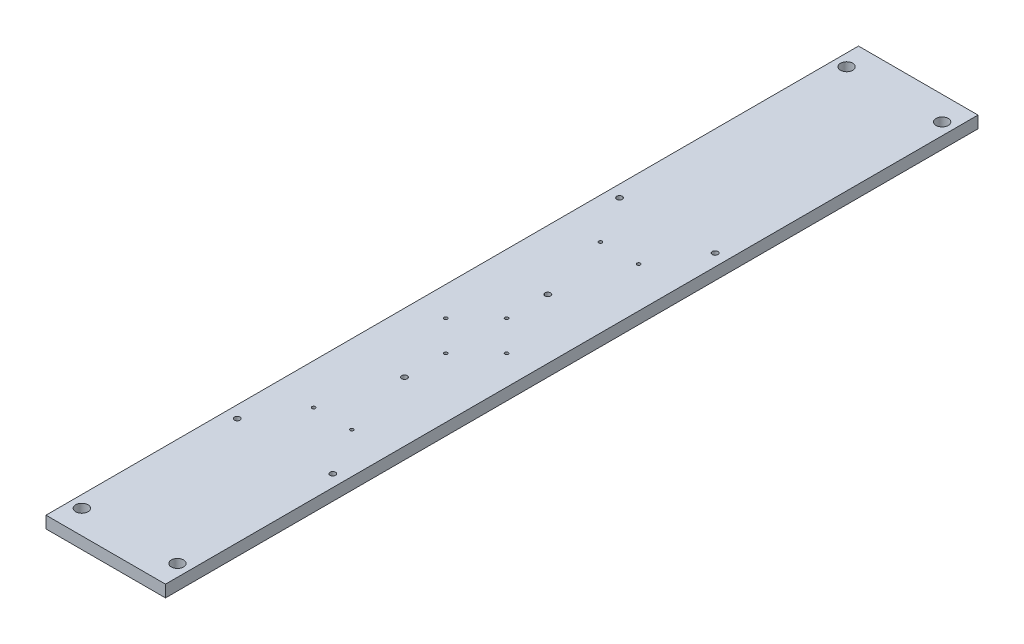
SolidWorks part; units mm, degrees
ref_plane "Front" through (0, 0, 0) normal (0, 0, 1) x (1, 0, 0)
ref_plane "Top" through (0, 0, 0) normal (0, 1, 0) x (1, 0, 0)
ref_plane "Right" through (0, 0, 0) normal (1, 0, 0) x (0, 0, -1)
sketch "Sketch1" plane through (0, 0, 0) normal (0, 1, 0) x (1, 0, 0)
  line L1 (0, 0) -> (63.5, 0)
  line L2 (0, 0) -> (0, 431.8)
  line L3 (0, 431.8) -> (63.5, 431.8)
  line L4 (63.5, 0) -> (63.5, 431.8)
  dimension "D1" = 431.8
  dimension "D2" = 63.5
extrude "Boss-Extrude1" add sketch "Sketch1" along normal blind 6.35
sketch "Sketch3" plane through (0, 6.35, 0) normal (0, 1, 0) x (1, 0, 0)
  line L0 (0, 0) -> (63.5, 0) construction
  line L1 (0, 431.8) -> (0, 0) construction
  line L2 (31.75, 431.8) -> (31.75, 0) construction
  line L3 (63.5, 431.8) -> (0, 431.8) construction
  line L6 (0, 165.1) -> (0, 228.6)
  line L9 (0, 196.85) -> (139.7, 196.85) construction
  circle A0 centre (3.175, 3.175) radius 1.1303
  circle A1 centre (3.175, 161.925) radius 1.1303
  circle A2 centre (3.175, 390.525) radius 1.1303
  circle A3 centre (3.175, 231.775) radius 1.1303
  circle A4 centre (60.325, 3.175) radius 1.1303
  circle A5 centre (60.325, 161.925) radius 1.1303
  circle A6 centre (60.325, 231.775) radius 1.1303
  circle A7 centre (60.325, 390.525) radius 1.1303
  dimension "D1" = 2.2606
  dimension "D2" = 3.175
  dimension "D3" = 3.175
  dimension "D5" = 63.5
  dimension "D4" = 2
sketch "Sketch6" plane through (0, 6.35, 0) normal (0, 1, 0) x (1, 0, 0)
  line L0 (63.5, 431.8) -> (0, 431.8) construction
  line L1 (0, 431.8) -> (0, 0) construction
  line L2 (31.75, 431.8) -> (31.75, 0) construction
  line L3 (0, 0) -> (63.5, 0) construction
  line L4 (31.75, 215.9) -> (94.2364, 215.9) construction
  circle A0 centre (6.35, 419.1) radius 3.2639
  circle A1 centre (57.15, 419.1) radius 3.2639
  circle A4 centre (57.15, 12.7) radius 3.2639
  circle A5 centre (6.35, 12.7) radius 3.2639
  point P13 (31.75, 215.9)
  dimension "D1" = 6.5278
  dimension "D2" = 12.7
  dimension "D3" = 6.35
extrude "Cut-Extrude9" cut sketch "Sketch6" against normal through all
sketch "Sketch7" plane through (0, 6.35, 0) normal (0, 1, 0) x (1, 0, 0)
  line L0 (0, 393.7) -> (63.5, 393.7) construction
  line L1 (0, 431.8) -> (0, 0) construction
  line L2 (63.5, 0) -> (63.5, 431.8) construction
  line L3 (0, 196.85) -> (139.7, 196.85) construction
  line L4 (31.75, 0) -> (31.75, 431.8) construction
  line L5 (0, 196.85) -> (63.5, 196.85) construction
  circle A0 centre (6.35, 298.45) radius 1.4732
  circle A1 centre (3.175, 390.525) radius 1.1303 construction
  circle A2 centre (57.15, 298.45) radius 1.4732
  circle A3 centre (57.15, 95.25) radius 1.4732
  circle A4 centre (6.35, 95.25) radius 1.4732
  circle A5 centre (31.75, 234.95) radius 1.4732
  circle A8 centre (31.75, 158.75) radius 1.4732
  dimension "D1" = 3.175
  dimension "D2" = 101.6
  dimension "D3" = 2.9464
  dimension "D4" = 6.35
  dimension "D5" = 2.9464
  dimension "D6" = 63.5
extrude "Cut-Extrude10" cut sketch "Sketch7" against normal through all
sketch "Sketch8" plane through (0, 6.35, 0) normal (0, 1, 0) x (1, 0, 0)
  line L0 (31.75, 0) -> (31.75, 431.8) construction
  line L1 (0, 196.85) -> (63.5, 196.85) construction
  line L2 (63.5, 0) -> (63.5, 431.8) construction
  circle A0 centre (15.5854, 196.85) radius 0.889
  circle A1 centre (31.75, 213.0146) radius 0.889
  circle A2 centre (47.9146, 196.85) radius 0.889
  circle A3 centre (31.75, 180.6854) radius 0.889
  circle A4 centre (21.59, 273.05) radius 0.889
  circle A5 centre (6.35, 298.45) radius 1.4732 construction
  circle A6 centre (41.91, 273.05) radius 0.889
  circle A7 centre (41.91, 120.65) radius 0.889
  circle A8 centre (21.59, 120.65) radius 0.889
  point P11 (31.75, 196.85)
  point P20 (31.75, 196.85)
  dimension "D1" = 1.778
  dimension "D2" = 16.1646
  dimension "D4" = 1.778
  dimension "D5" = 25.4
  dimension "D6" = 10.16
  dimension "D3" = 4
extrude "Cut-Extrude11" cut sketch "Sketch8" against normal through all
